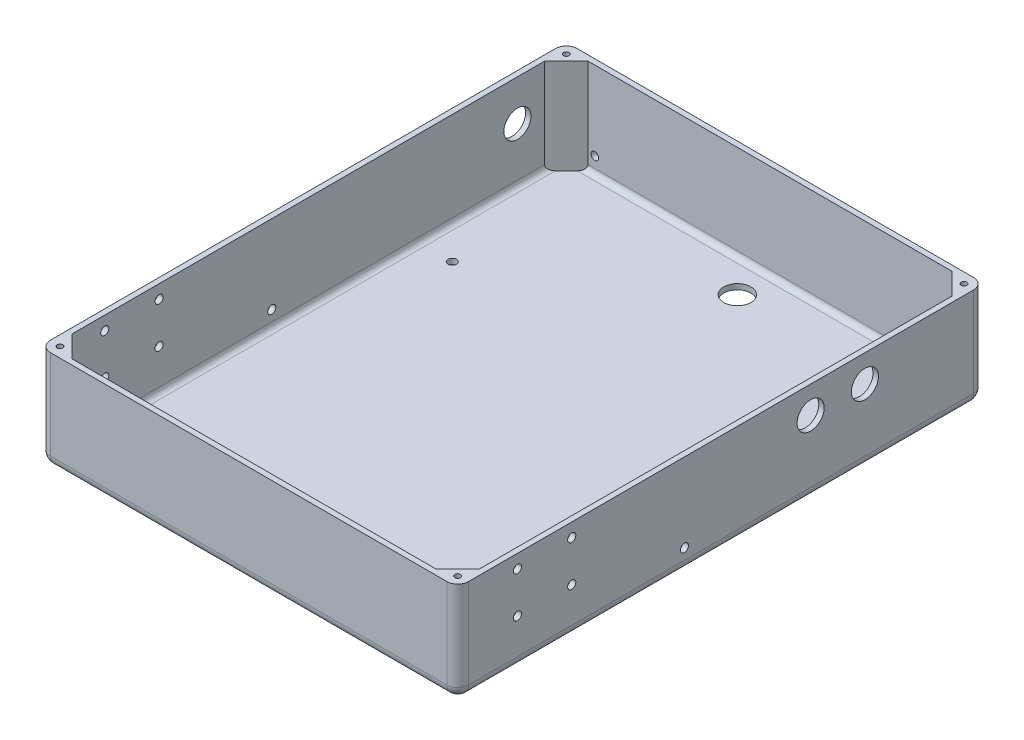
SolidWorks part; units mm, degrees
ref_plane "Front Plane" through (0, 0, 0) normal (0, 0, 1) x (1, 0, 0)
ref_plane "Top Plane" through (0, 0, 0) normal (0, 1, 0) x (1, 0, 0)
ref_plane "Right Plane" through (0, 0, 0) normal (1, 0, 0) x (0, 0, -1)
sketch "Sketch1" plane through (0, 0, 0) normal (0, 1, 0) x (1, 0, 0)
  line L1 (-95.25, 120.65) -> (95.25, 120.65)
  line L2 (-95.25, 120.65) -> (-95.25, -120.65)
  line L3 (-95.25, -120.65) -> (95.25, -120.65)
  line L4 (95.25, 120.65) -> (95.25, -120.65)
  point P4 (0, 120.65)
  point P6 (-95.25, 0)
  dimension "D1" = 241.3
  dimension "D2" = 190.5
extrude "Boss-Extrude1" add sketch "Sketch1" along normal blind 44.45
fillet "Fillet1" radius 2.54 8 edges at (0, 0, 120.65) (95.25, 0, 0) (0, 0, -120.65) (-95.25, 0, 0) (95.25, 22.225, 120.65) (-95.25, 22.225, 120.65) (95.25, 22.225, -120.65) (-95.25, 22.225, -120.65)
shell "Shell1" thickness 2.54
ref_plane "Plane1" through (0, 0, 101.6) normal (0, 0, 1) x (1, 0, 0)
sketch "Sketch2" plane through (0, 0, 101.6) normal (0, 0, 1) x (1, 0, 0)
  line L0 (104.14, 2.54) -> (165.1, 2.54)
  line L1 (165.1, 2.54) -> (165.1, -2.54)
  line L2 (165.1, -2.54) -> (92.71, -2.54)
  line L5 (97.79, 8.89) -> (97.79, 2.54)
  line L6 (97.79, 2.54) -> (92.71, -2.54)
  line L8 (97.79, 44.45) -> (97.79, 2.54) construction
  arc A0 (104.14, 2.54) -> (97.79, 8.89) centre (104.14, 8.89) cw
  arc A1 (92.71, -2.54) -> (97.79, 2.54) centre (92.71, 2.54) ccw construction
  dimension "D2" = 6.35
  dimension "D1" = 165.1
  dimension "D3" = 5.08
hole_wizard "Hole A" positions "Sketch10" profile "Sketch11" hole size "Ø4.0" standard "ANSI Metric" end condition through all
sketch "Sketch10" plane through (0, 0, 0) normal (0, 1, 0) x (1, 0, 0)
  line L2 (-92.71, -118.11) -> (-92.71, 118.11) construction
  line L3 (92.71, -118.11) -> (-92.71, -118.11) construction
  point P0 (-80.01, 52.07)
  point P2 (74.91, 52.07)
  point P4 (-80.01, -105.41)
  point P6 (52.07, -105.41)
  dimension "D1" = 154.92
  dimension "D2" = 157.48
  dimension "D3" = 12.7
  dimension "D4" = 12.7
  dimension "D5" = 132.08
sketch "Sketch11" plane through (-80.01, 0, -52.07) normal (1, 0, 0) x (0, 0, 1)
  line L0 (0, 0) -> (0, 2.54)
  line L1 (0, 2.54) -> (2, 2.54)
  line L2 (2, 2.54) -> (2, 0)
  line L5 (2, 0) -> (0, 0)
  line L11 (0, -6.35) -> (0, 107.95) construction
  dimension "Thru Hole Dia." = 4
  dimension "Thru Hole Depth" = 2.54
sketch "Sketch25" plane through (0, 44.45, 0) normal (0, 1, 0) x (1, 0, 0)
  line L0 (85.09, 120.65) -> (95.25, 110.49)
  line L1 (92.71, 120.65) -> (-92.71, 120.65) construction
  line L2 (95.25, -118.11) -> (95.25, 118.11) construction
  line L3 (95.25, 110.49) -> (95.25, 120.65)
  line L4 (95.25, 120.65) -> (85.09, 120.65)
  dimension "D1" = 10.16
extrude "Boss-Extrude3" add sketch "Sketch25" against normal up to surface (44.45 mm away) up to face at (-80.01, 0, -50.07)
mirror "Mirror2" about plane through (0, 0, 0) normal (0, 0, 1) of "Boss-Extrude3"
mirror "Mirror3" about plane through (0, 0, 0) normal (1, 0, 0) of "Mirror2", "Boss-Extrude3"
hole_wizard "Cover Holes" positions "Sketch28" profile "Sketch29" hole size "9/64" standard "ANSI Inch"
sketch "Sketch28" plane through (0, 44.45, 0) normal (0, 1, 0) x (1, 0, 0)
  line L0 (92.71, 123.19) -> (-92.71, 123.19) construction
  line L1 (97.79, -118.11) -> (97.79, 118.11) construction
  line L2 (-97.79, 118.11) -> (-97.79, -118.11) construction
  line L3 (-92.71, -123.19) -> (92.71, -123.19) construction
  point P0 (-93.0275, 118.4275)
  point P2 (-93.0275, -118.4275)
  point P4 (93.0275, -118.4275)
  point P6 (93.0275, 118.4275)
  dimension "D1" = 4.7625
  dimension "D2" = 4.7625
  dimension "D3" = 4.7625
  dimension "D4" = 4.7625
sketch "Sketch29" plane through (-93.0275, 44.45, -118.4275) normal (1, 0, 0) x (0, 0, 1)
  line L0 (0, 0) -> (0, 13.4951)
  line L1 (0, 13.4951) -> (1.3233, 12.7)
  line L2 (1.3233, 12.7) -> (1.3233, 0)
  line L5 (1.3233, 0) -> (0, 0)
  line L10 (0, 13.4951) -> (-1.3233, 12.7) construction
  line L11 (0, -6.35) -> (0, 107.95) construction
  dimension "Hole Dia." = 2.6467
  dimension "Hole Depth" = 12.7
  dimension "Drill Angle" = 118
hole_wizard "Hole for wiring" positions "Sketch30" profile "Sketch31" hole size "1/2" standard "ANSI Inch" end condition through all
sketch "Sketch30" plane through (0, 0, 0) normal (0, 1, 0) x (1, 0, 0)
  line L0 (-87.63, 118.11) -> (87.63, 118.11) construction
  line L2 (0, -25.8445) -> (0, 25.8445) construction
  point P0 (0, 105.41)
  dimension "D1" = 12.7
  dimension "D2" = 0
sketch "Sketch31" plane through (0, 0, -105.41) normal (1, 0, 0) x (0, 0, 1)
  line L0 (0, 0) -> (0, 2.54)
  line L1 (0, 2.54) -> (6.35, 2.54)
  line L2 (6.35, 2.54) -> (6.35, 0)
  line L5 (6.35, 0) -> (0, 0)
  line L11 (0, -6.35) -> (0, 107.95) construction
  dimension "Thru Hole Dia." = 12.7
  dimension "Thru Hole Depth" = 2.54
hole_wizard "Hole to outside wiring" positions "Sketch32" profile "Sketch33" hole size "1/2" standard "ANSI Inch"
sketch "Sketch32" plane through (-97.79, 0, 0) normal (-1, 0, 0) x (0, 0, 1)
  line L0 (-118.11, 44.45) -> (118.11, 44.45) construction
  line L1 (-123.19, 2.54) -> (-123.19, 44.45) construction
  point P0 (-97.79, 25.4)
  dimension "D1" = 19.05
  dimension "D2" = 25.4
sketch "Sketch33" plane through (-97.79, 25.4, -97.79) normal (0, 1, 0) x (0, 0, 1)
  line L0 (0, 0) -> (0, 6.3555)
  line L1 (0, 6.3555) -> (6.35, 2.54)
  line L2 (6.35, 2.54) -> (6.35, 0)
  line L5 (6.35, 0) -> (0, 0)
  line L10 (0, 6.3555) -> (-6.35, 2.54) construction
  line L11 (0, -6.35) -> (0, 107.95) construction
  dimension "Hole Dia." = 12.7
  dimension "Hole Depth" = 2.54
  dimension "Drill Angle" = 118
hole_wizard "9/64 (0.15) Diameter Hole1" positions "Sketch34" profile "Sketch35" hole size "9/64" standard "ANSI Inch" end condition through all
sketch "Sketch34" plane through (97.79, 0, 0) normal (1, 0, 0) x (0, 0, -1)
  line L0 (-123.19, 2.54) -> (-123.19, 44.45) construction
  line L1 (118.11, -2.54) -> (-118.11, -2.54) construction
  point P0 (-17.145, 7.62)
  dimension "D1" = 106.045
  dimension "D2" = 10.16
sketch "Sketch35" plane through (97.79, 7.62, 17.145) normal (0, 1, 0) x (0, 0, -1)
  line L0 (0, 0) -> (0, 195.58)
  line L1 (0, 195.58) -> (1.905, 195.58)
  line L2 (1.905, 195.58) -> (1.905, 0)
  line L5 (1.905, 0) -> (0, 0)
  line L11 (0, -6.35) -> (0, 107.95) construction
  dimension "Thru Hole Dia." = 3.81
  dimension "Thru Hole Depth" = 195.58
hole_wizard "9/64 (0.14063) Diameter Hole2" positions "Sketch36" profile "Sketch37" hole size "9/64" standard "ANSI Inch"
sketch "Sketch36" plane through (0, 0, -123.19) normal (0, 0, -1) x (-1, 0, 0)
  line L0 (-97.79, 2.54) -> (-97.79, 44.45) construction
  line L1 (92.71, -2.54) -> (-92.71, -2.54) construction
  line L2 (97.79, 44.45) -> (97.79, 2.54) construction
  point P0 (-81.915, 7.62)
  point P2 (81.915, 7.62)
  dimension "D1" = 15.875
  dimension "D2" = 10.16
  dimension "D3" = 15.875
sketch "Sketch37" plane through (81.915, 7.62, -123.19) normal (1, 0, 0) x (0, 1, 0)
  line L0 (0, 0) -> (0, 3.6131)
  line L1 (0, 3.6131) -> (1.786, 2.54)
  line L2 (1.786, 2.54) -> (1.786, 0)
  line L5 (1.786, 0) -> (0, 0)
  line L10 (0, 3.6131) -> (-1.786, 2.54) construction
  line L11 (0, -6.35) -> (0, 107.95) construction
  dimension "Hole Dia." = 3.572
  dimension "Hole Depth" = 2.54
  dimension "Drill Angle" = 118
hole_wizard "Antenna Holes" positions "Sketch38" profile "Sketch39" hole size "1/2" standard "ANSI Inch"
sketch "Sketch38" plane through (97.79, 0, 0) normal (1, 0, 0) x (0, 0, -1)
  line L0 (118.11, 2.54) -> (118.11, 44.45) construction
  line L1 (-118.11, 44.45) -> (118.11, 44.45) construction
  point P0 (67.31, 31.75)
  point P2 (41.91, 31.75)
  dimension "D1" = 50.8
  dimension "D2" = 12.7
  dimension "D3" = 25.4
sketch "Sketch39" plane through (97.79, 31.75, -67.31) normal (0, 1, 0) x (0, 0, -1)
  line L0 (0, 0) -> (0, 6.3555)
  line L1 (0, 6.3555) -> (6.35, 2.54)
  line L2 (6.35, 2.54) -> (6.35, 0)
  line L5 (6.35, 0) -> (0, 0)
  line L10 (0, 6.3555) -> (-6.35, 2.54) construction
  line L11 (0, -6.35) -> (0, 107.95) construction
  dimension "Hole Dia." = 12.7
  dimension "Hole Depth" = 2.54
  dimension "Drill Angle" = 118
hole_wizard "1/8 (0.15) Diameter Hole1" positions "Sketch40" profile "Sketch41" hole size "1/8" standard "ANSI Inch" end condition through all
sketch "Sketch40" plane through (97.79, 0, 0) normal (1, 0, 0) x (0, 0, -1)
  line L0 (-101.6, 23.0505) -> (-101.6, -23.0505) construction
  line L1 (-118.11, 44.45) -> (118.11, 44.45) construction
  point P0 (-95.25, 38.1)
  point P2 (-69.85, 38.1)
  point P4 (-95.25, 19.05)
  point P6 (-69.85, 19.05)
  dimension "D1" = 6.35
  dimension "D2" = 6.35
  dimension "D3" = 25.4
  dimension "D4" = 19.05
sketch "Sketch41" plane through (97.79, 38.1, 95.25) normal (0, 1, 0) x (0, 0, -1)
  line L0 (0, 0) -> (0, 195.58)
  line L1 (0, 195.58) -> (1.905, 195.58)
  line L2 (1.905, 195.58) -> (1.905, 0)
  line L5 (1.905, 0) -> (0, 0)
  line L11 (0, -6.35) -> (0, 107.95) construction
  dimension "Thru Hole Dia." = 3.81
  dimension "Thru Hole Depth" = 195.58
